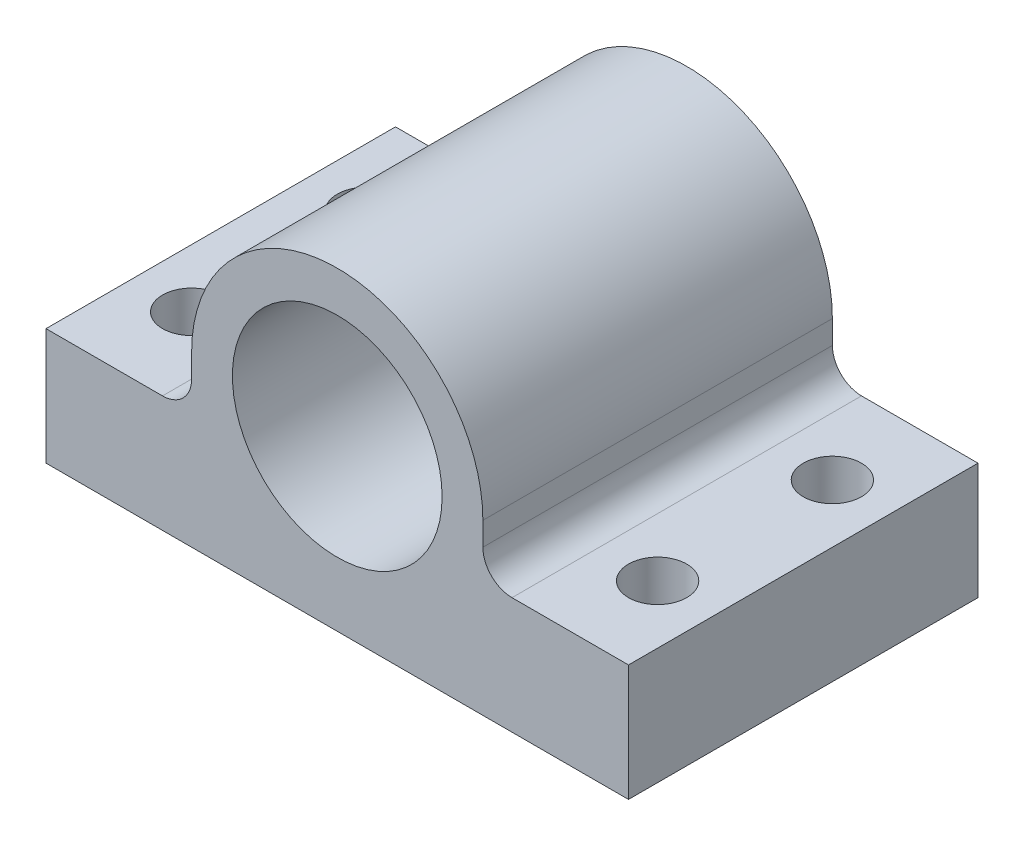
SolidWorks part; units mm, degrees
ref_plane "Front Plane" through (0, 0, 0) normal (0, 0, 1) x (1, 0, 0)
ref_plane "Top Plane" through (0, 0, 0) normal (0, 1, 0) x (1, 0, 0)
ref_plane "Right Plane" through (0, 0, 0) normal (1, 0, 0) x (0, 0, -1)
sketch "Sketch1" plane through (0, 0, 0) normal (0, 0, 1) x (1, 0, 0)
  line L0 (0, 0) -> (0, 14.5) construction
  line L1 (0, 0) -> (-25, 0)
  line L2 (0, 0) -> (25, 0)
  line L3 (-25, 10) -> (-25, 0)
  line L4 (0, 14.5) -> (0, 30) construction
  line L5 (-12.5, 12.5) -> (-12.5, 14.5)
  line L6 (12.5, 12.5) -> (12.5, 14.5)
  line L7 (-15, 10) -> (-25, 10)
  line L9 (25, 10) -> (25, 0)
  line L10 (15, 10) -> (25, 10)
  circle A0 centre (0, 14.5) radius 9
  arc A1 (15, 10) -> (12.5, 12.5) centre (15, 12.5) cw
  arc A2 (-15, 10) -> (-12.5, 12.5) centre (-15, 12.5) ccw
  arc A3 (12.5, 14.5) -> (-12.5, 14.5) centre (0, 14.5) ccw
  point P15 (12.5, 10)
  point P18 (-12.5, 10)
  point P21 (12.5, 30)
  point P24 (-12.5, 30)
  dimension "D1" = 2.5
extrude "Boss-Extrude1" add sketch "Sketch1" along normal blind 30
sketch "Sketch3" plane through (0, 10, 0) normal (0, 1, 0) x (1, 0, 0)
  line L0 (-25, -15) -> (-20, -15) construction
  line L1 (-25, -30) -> (-25, 0) construction
  line L2 (0, 0) -> (0, 7.2935) construction
  line L3 (-20, -15) -> (-20, -7.5) construction
  circle A0 centre (-20, -7.5) radius 2.5
  circle A1 centre (-20, -22.5) radius 2.5
  circle A2 centre (20, -22.5) radius 2.5
  circle A3 centre (20, -7.5) radius 2.5
extrude "Cut-Extrude1" cut sketch "Sketch3" against normal blind 17.65
